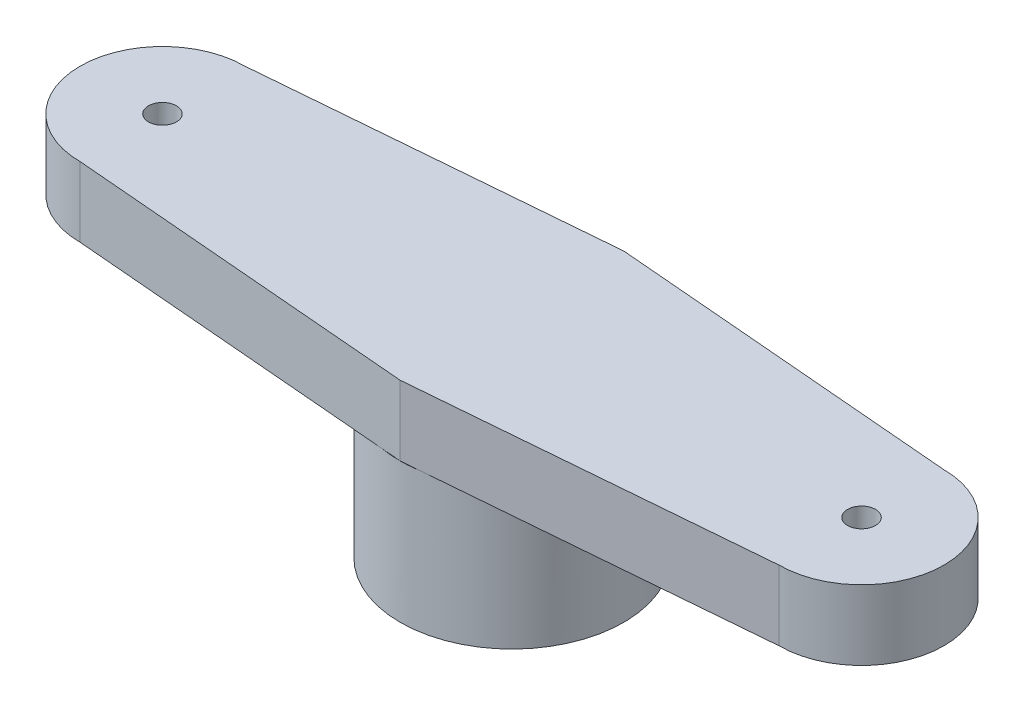
SolidWorks part; units mm, degrees
ref_plane "Front Plane" through (0, 0, 0) normal (0, 0, 1) x (1, 0, 0)
ref_plane "Top Plane" through (0, 0, 0) normal (0, 1, 0) x (1, 0, 0)
ref_plane "Right Plane" through (0, 0, 0) normal (1, 0, 0) x (0, 0, -1)
sketch "Sketch2" plane through (0, 0, 0) normal (0, 1, 0) x (1, 0, 0)
  circle A0 centre (0, 0) radius 5.25
  circle A1 centre (0, 0) radius 8
  dimension "D1" = 10.5
  dimension "D2" = 16
extrude "Boss-Extrude1" add sketch "Sketch2" along normal blind 10
sketch "Sketch3" plane through (0, 10, 0) normal (0, 1, 0) x (1, 0, 0)
  line L0 (0, 0) -> (25, 0) construction
  line L1 (25, 0) -> (-25, 0) construction
  line L2 (0, 8) -> (-25, 5.9015)
  line L3 (-25, -5.9015) -> (0, -8)
  line L4 (0, 8) -> (0, -11.5322) construction
  line L5 (25, -5.9015) -> (0, -8)
  line L6 (0, 8) -> (25, 5.9015)
  circle A0 centre (0, 0) radius 8 construction
  arc A1 (-25, 5.9015) -> (-25, -5.9015) centre (-25, 0) ccw
  arc A2 (25, 5.9015) -> (25, -5.9015) centre (25, 0) cw
  dimension "D1" = 25
  dimension "D2" = 50
extrude "Boss-Extrude2" add sketch "Sketch3" along normal blind 5
sketch "Sketch4" plane through (0, 15, 0) normal (0, 1, 0) x (1, 0, 0)
  circle A0 centre (-25, 0) radius 1
  circle A1 centre (25, 0) radius 1
  dimension "D1" = 2
  dimension "D2" = 2
extrude "Cut-Extrude1" cut sketch "Sketch4" against normal blind 5
